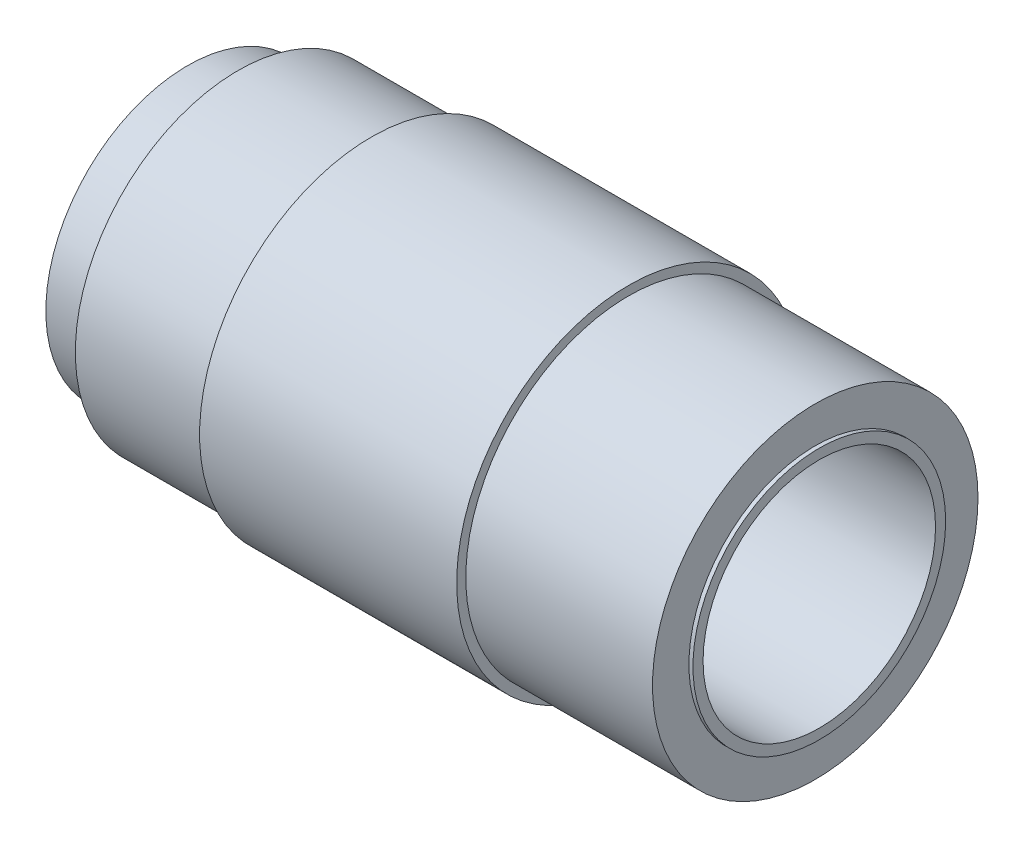
SolidWorks part; units mm, degrees
material "Pure Lead"
ref_plane "Front Plane" through (0, 0, 0) normal (0, 0, 1) x (1, 0, 0)
ref_plane "Top Plane" through (0, 0, 0) normal (0, 1, 0) x (1, 0, 0)
ref_plane "Right Plane" through (0, 0, 0) normal (1, 0, 0) x (0, 0, -1)
sketch "Sketch1" plane through (0, 0, 0) normal (0, 1, 0) x (1, 0, 0)
  line L0 (0, 0) -> (-43.3435, 0) construction
  line L1 (-37.5, 12.5) -> (-37.5, 11.5)
  line L2 (-37.5, 12.5) -> (-37.9, 12.5)
  line L3 (-37.9, 12.5) -> (-37.9, 16.1)
  line L4 (-37.9, 16.1) -> (-56.3734, 16.1)
  line L5 (-56.3734, 16.1) -> (-56.3734, 17)
  line L6 (-56.3734, 17) -> (-81.8085, 17)
  line L7 (-81.8085, 17) -> (-81.8085, 16.1)
  line L8 (-81.8085, 16.1) -> (-95, 16.1)
  line L9 (-95, 16.1) -> (-95, 14.0176)
  line L10 (-95, 14.0176) -> (-100, 14.0176)
  line L11 (-100, 14.0176) -> (-100, 11.5)
  line L12 (-100, 11.5) -> (-37.5, 11.5)
  dimension "D1" = 37.5
  dimension "D2" = 57.5
  dimension "D3" = 5
  dimension "D4" = 0.4
  dimension "D5" = 34
  dimension "D6" = 32.2
  dimension "D7" = 25
  dimension "D8" = 1
revolve "Revolve1" add sketch "Sketch1" angle 360 about L0
